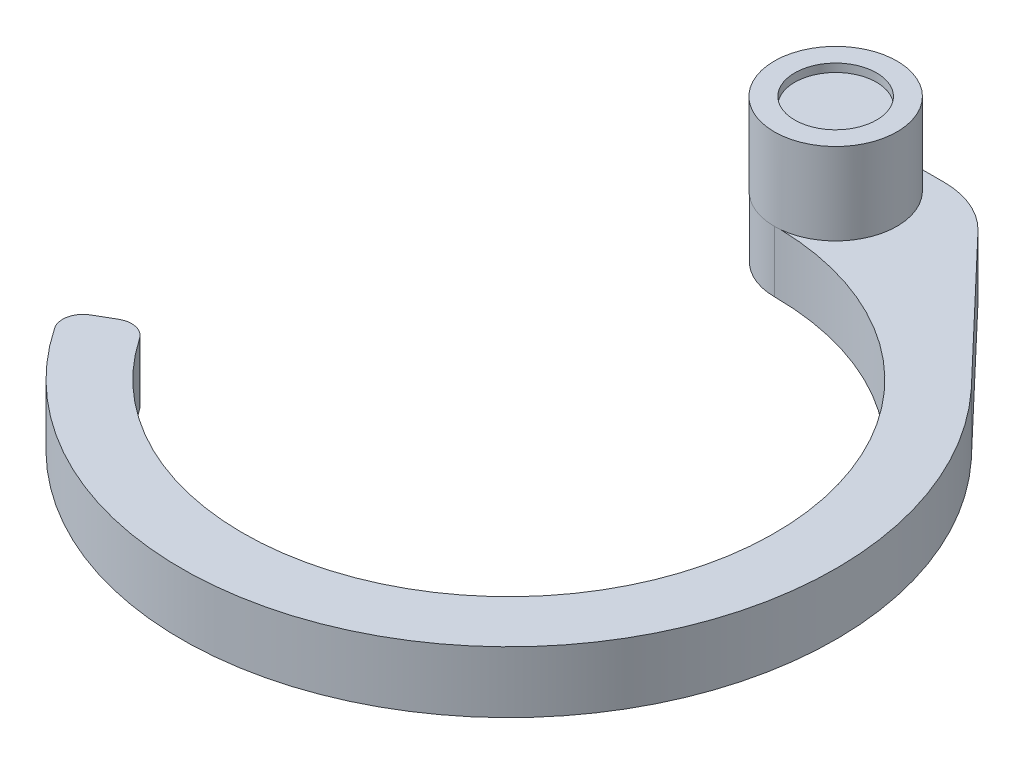
SolidWorks part; units mm, degrees
ref_plane "正面" through (0, 0, 0) normal (0, 0, 1) x (1, 0, 0)
ref_plane "平面" through (0, 0, 0) normal (0, 1, 0) x (1, 0, 0)
ref_plane "右側面" through (0, 0, 0) normal (1, 0, 0) x (0, 0, -1)
sketch "ｽｹｯﾁ2" plane through (0, 0, 0) normal (0, 1, 0) x (1, 0, 0)
  line L1 (-1.8089, 2.6033) -> (0, 0)
  line L2 (-60.4669, -34.9106) -> (-64.8074, -37.4166)
  line L4 (0, 95) -> (11.4274, 95)
  line L5 (25.9115, 88.7917) -> (58.5757, 54.4875)
  arc A0 (-66.4612, -44.5298) -> (57.2894, 55.8384) centre (0, 0) ccw
  arc A1 (-53.8264, -36.4378) -> (0, 65) centre (0, 0) ccw
  arc A2 (0, 95) -> (0, 65) centre (0, 80) ccw
  arc A3 (11.4274, 95) -> (25.9115, 88.7917) centre (11.4274, 75) cw
  arc A4 (-53.8264, -36.4378) -> (-60.4669, -34.9106) centre (-57.9669, -39.2407) ccw
  arc A5 (-66.4612, -44.5298) -> (-64.8074, -37.4166) centre (-62.3074, -41.7467) cw
  dimension "D1" = 160
  dimension "D2" = 130
  dimension "D4" = 20
  dimension "D5" = 5
  dimension "D6" = 5
extrude "ﾎﾞｽ - 押し出し4" add sketch "ｽｹｯﾁ2" along normal blind 15 contours A5 A0 L5 A3 L4 A2 A1 A4 L2
sketch "ｽｹｯﾁ10" plane through (0, 15, 0) normal (0, 1, 0) x (1, 0, 0)
  circle A0 centre (0, 79.9067) radius 15
  dimension "D1" = 30
extrude "ﾎﾞｽ - 押し出し5" add sketch "ｽｹｯﾁ10" along normal blind 20
sketch "ｽｹｯﾁ11" plane through (0, 35, 0) normal (0, 1, 0) x (1, 0, 0)
  circle A0 centre (0, 79.9067) radius 10
  dimension "D1" = 20
extrude "ｶｯﾄ - 押し出し1" cut sketch "ｽｹｯﾁ11" against normal blind 2
